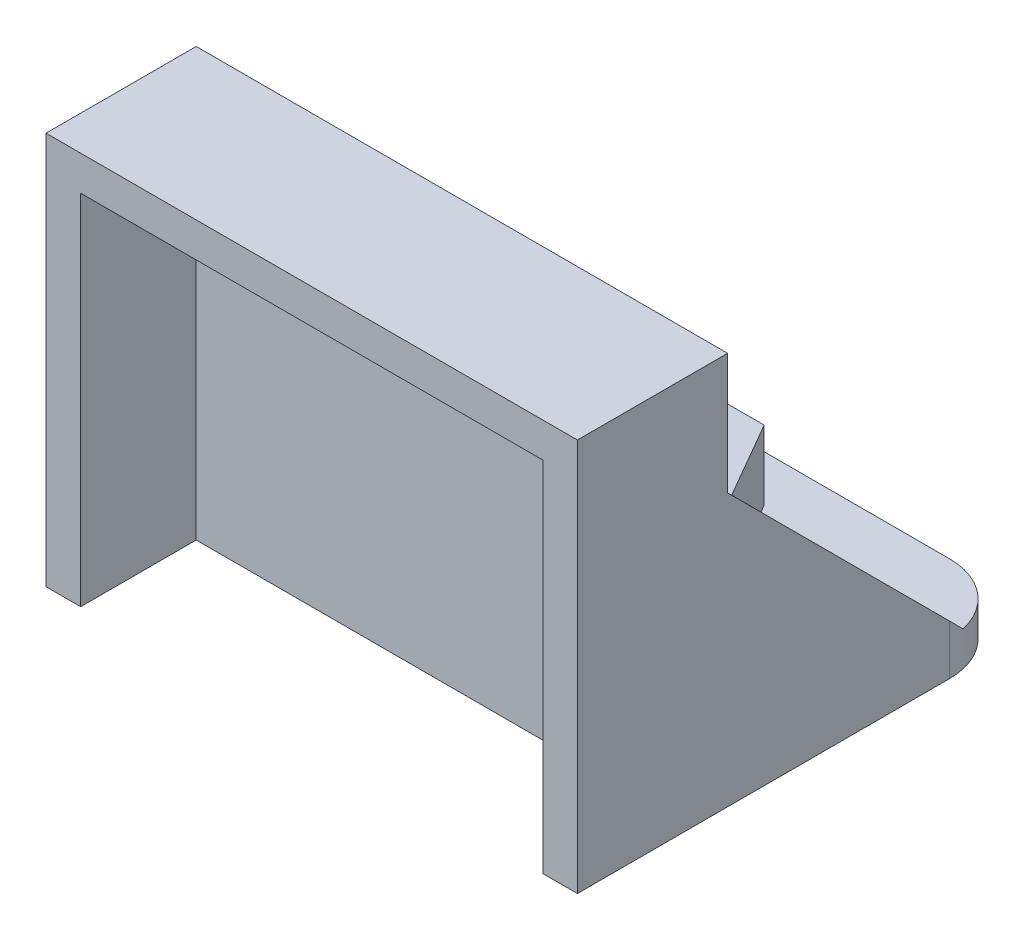
SolidWorks part; units mm, degrees
ref_plane "前视基准面" through (0, 0, 0) normal (0, 0, 1) x (1, 0, 0)
ref_plane "上视基准面" through (0, 0, 0) normal (0, 1, 0) x (1, 0, 0)
ref_plane "右视基准面" through (0, 0, 0) normal (1, 0, 0) x (0, 0, -1)
sketch "草图1" plane through (0, 0, 0) normal (0, 0, 1) x (1, 0, 0)
  line L1 (-11.5, 8.5) -> (11.5, 8.5)
  line L2 (-11.5, 8.5) -> (-11.5, -8.5)
  line L3 (-11.5, -8.5) -> (11.5, -8.5)
  line L4 (11.5, 8.5) -> (11.5, -8.5)
  line L5 (-11.5, 8.5) -> (11.5, -8.5) construction
  line L6 (-11.5, -8.5) -> (11.5, 8.5) construction
  point P0 (0, 0)
  dimension "D1" = 23
  dimension "D2" = 17
extrude "凸台-拉伸1" add sketch "草图1" along normal blind 6.5
sketch "草图2" plane through (0, 0, 6.5) normal (0, 0, 1) x (1, 0, 0)
  line L0 (0, -3.575) -> (0, 3.575) construction
  line L1 (-10, 7) -> (10, 7)
  line L2 (-10, 7) -> (-10, -8.5)
  line L3 (-10, -8.5) -> (10, -8.5)
  line L4 (10, 7) -> (10, -8.5)
  line L5 (-10, 7) -> (10, -8.5) construction
  line L6 (-10, -8.5) -> (10, 7) construction
  line L7 (-11.5, -8.5) -> (11.5, -8.5) construction
  line L8 (11.5, 8.5) -> (-11.5, 8.5) construction
  line L9 (-11.5, 8.5) -> (-11.5, -8.5) construction
  line L10 (11.5, -8.5) -> (11.5, 8.5) construction
  point P0 (0, -0.75)
  dimension "D1" = 1.5
  dimension "D2" = 1.5
  dimension "D3" = 1.5
extrude "切除-拉伸1" cut sketch "草图2" against normal blind 5
sketch "草图3" plane through (0, 0, 0) normal (0, 0, -1) x (-1, 0, 0)
  line L0 (-11.5, -8.5) -> (-11.5, 8.5) construction
  line L1 (-11.5, -7) -> (11.5, -7)
  line L2 (-11.5, -7) -> (-11.5, -8.5)
  line L3 (-11.5, -8.5) -> (11.5, -8.5)
  line L4 (11.5, -7) -> (11.5, -8.5)
  dimension "D1" = 1.5
extrude "凸台-拉伸2" add sketch "草图3" along normal blind 12.6
sketch "草图4" plane through (0, -7, 0) normal (0, 1, 0) x (1, 0, 0)
  line L0 (4.9652, 6.3) -> (2.4826, 10.6)
  line L1 (3.2332, 6.3) -> (1.6166, 9.1)
  line L2 (1.6166, 9.1) -> (-1.6166, 9.1)
  line L3 (-1.6166, 9.1) -> (-3.2332, 6.3)
  line L4 (-3.2332, 6.3) -> (-1.6166, 3.5)
  line L5 (-1.6166, 3.5) -> (1.6166, 3.5)
  line L6 (1.6166, 3.5) -> (3.2332, 6.3)
  line L7 (2.4826, 10.6) -> (-2.4826, 10.6)
  line L8 (-2.4826, 10.6) -> (-4.9652, 6.3)
  line L9 (-4.9652, 6.3) -> (-2.4826, 2)
  line L10 (-2.4826, 2) -> (2.4826, 2)
  line L11 (2.4826, 2) -> (4.9652, 6.3)
  line L12 (0, -9.35) -> (0, 9.35) construction
  line L13 (-11.5, 0) -> (11.5, 0) construction
  line L14 (-11.5, 12.6) -> (11.5, 12.6) construction
  circle A0 centre (0, 6.3) radius 2.8 construction
  dimension "D1" = 5.6
  dimension "D3" = 2
  dimension "D4" = 2
  dimension "D2" = 1.5
extrude "凸台-拉伸3" add sketch "草图4" along normal blind 3
ref_plane "基准面4" through (0, -3.5, -3.5) normal (0, -0.7071, -0.7071) x (-1, 0, 0)
sketch "草图7" plane through (0, -3.5, -3.5) normal (0, -0.7071, -0.7071) x (-1, 0, 0)
  line L0 (-11.5, -10.6066) -> (-11.5, 2.8991) construction
  line L1 (-10, -4.9497) -> (-11.5, -4.9497)
  line L2 (-10, -4.9497) -> (-10, 2.3101)
  line L3 (-10, 2.3101) -> (-11.5, 2.3101)
  line L4 (-11.5, -4.9497) -> (-11.5, 2.3101)
  line L5 (11.5, -4.9497) -> (-11.5, -4.9497) construction
  dimension "D1" = 1.5
extrude "凸台-拉伸6" add sketch "草图7" along normal up to surface and the other way up to surface up to face at (0, -7, -6.3) other way up to face at (0, 0.75, 0)
mirror "镜向1" about plane through (0, 0, 0) normal (1, 0, 0) of "凸台-拉伸6"
hole_wizard "M3 间隙孔1" positions "草图8" profile "草图9" hole size "M3" standard "ISO" end condition up to next
sketch "草图8" plane through (0, -7, 0) normal (0, 1, 0) x (1, 0, 0)
  point P0 (0, 6.3)
sketch "草图9" plane through (0, -7, -6.3) normal (1, 0, 0) x (0, 0, 1)
  line L0 (0, 0) -> (0, 1.5)
  line L1 (0, 1.5) -> (1.6, 1.5)
  line L2 (1.6, 1.5) -> (1.6, 0)
  line L5 (1.6, 0) -> (0, 0)
  line L11 (0, -6.35) -> (0, 107.95) construction
  dimension "通孔孔直径" = 3.2
  dimension "通孔孔深度" = 1.5
fillet "圆角1" radius 3 2 edges at (-11.5, -7.75, -12.6) (11.5, -7.75, -12.6)
